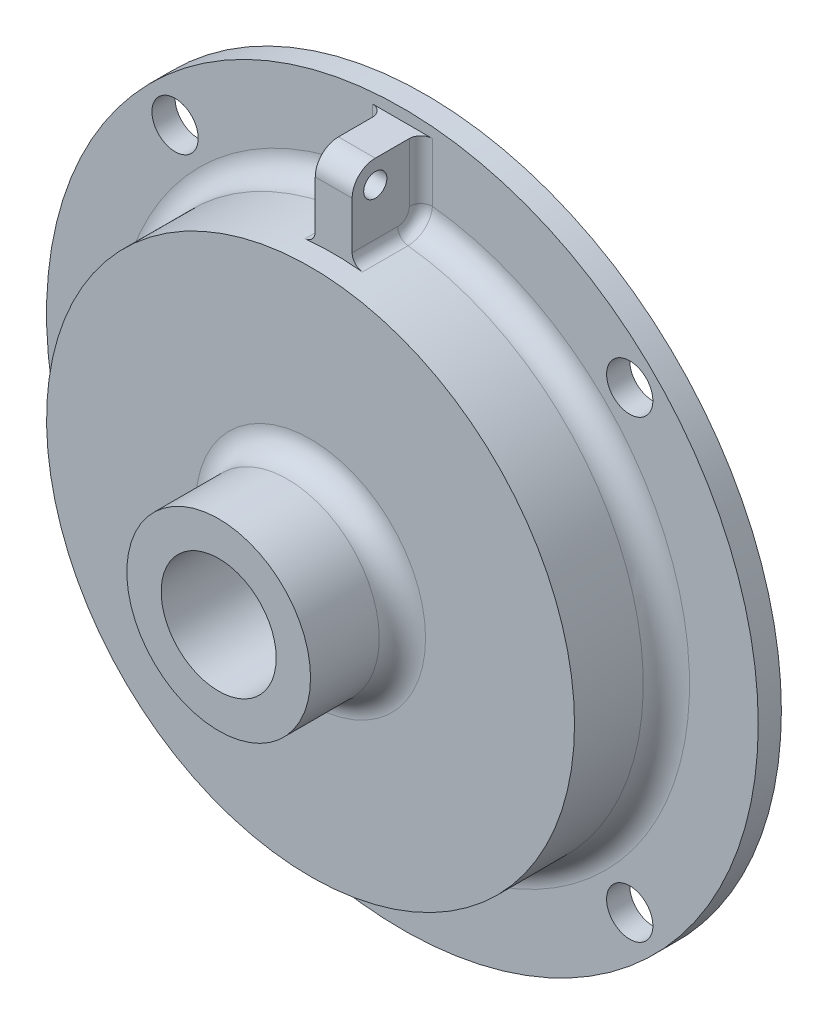
SolidWorks part; units mm, degrees
material "PW40:6:Sc:0:Re:24:"
ref_plane "Front" through (0, 0, 0) normal (0, 0, 1) x (1, 0, 0)
ref_plane "Top" through (0, 0, 0) normal (0, 1, 0) x (1, 0, 0)
ref_plane "Right" through (0, 0, 0) normal (1, 0, 0) x (0, 0, -1)
sketch "Sketch1" plane through (0, 0, 0) normal (0, 0, 1) x (1, 0, 0)
  circle A0 centre (0, 0) radius 49.2
  dimension "D1" = 98.4
extrude "Base-Extrude" add sketch "Sketch1" along normal blind 3.2
sketch "Sketch5" plane through (0, 0, 3.2) normal (0, 0, 1) x (1, 0, 0)
  line L0 (31.4309, 31.4309) -> (0, 0) construction
  line L1 (0, 0) -> (44.45, 0) construction
  circle A0 centre (0, 0) radius 44.45 construction
  circle A1 centre (31.4309, 31.4309) radius 3.2
  dimension "D1" = 88.9
  dimension "D2" = 6.4
  dimension "D3" = 45
extrude "Cut-Extrude2" cut sketch "Sketch5" against normal through all
pattern_circular "CirPattern1" count 4 every 90 about axis through (0, 0, 0) along (0, 0, 1) of "Cut-Extrude2"
sketch "Sketch2" plane through (0, 0, 3.2) normal (0, 0, 1) x (1, 0, 0)
  circle A0 centre (0, 0) radius 36.5
  dimension "D1" = 73
extrude "Boss-Extrude1" add sketch "Sketch2" along normal blind 12.7
sketch "Sketch3" plane through (0, 0, 15.9) normal (0, 0, 1) x (1, 0, 0)
  circle A0 centre (0, 0) radius 12.7
  dimension "D1" = 25.4
extrude "Boss-Extrude2" add sketch "Sketch3" along normal blind 12.7
fillet "Fillet1" radius 3.2 2 edges at (36.5, 0, 3.2) (12.7, 0, 15.9)
sketch "Sketch6" plane through (0, 0, 0) normal (0, 1, 0) x (1, 0, 0)
  line L0 (-2.55, -3.2) -> (-2.55, -12.7)
  line L1 (-39.7, -3.2) -> (39.7, -3.2) construction
  line L2 (-2.55, -3.2) -> (2.55, -3.2)
  line L3 (-49.2, -3.2) -> (49.2, -3.2) construction
  line L4 (2.55, -3.2) -> (2.55, -12.7)
  line L5 (-2.55, -12.7) -> (2.55, -12.7)
  line L6 (0, 0) -> (0, -38.11) construction
  line L7 (0, -3.2) -> (0, 0) construction
  dimension "D1" = 5.1
  dimension "D2" = 9.5
extrude "Boss-Extrude3" add sketch "Sketch6" along normal blind 47.6
sketch "Sketch4" plane through (0, 0, 28.6) normal (0, 0, 1) x (1, 0, 0)
  circle A0 centre (0, 0) radius 7.95
  dimension "D1" = 15.9
extrude "Cut-Extrude1" cut sketch "Sketch4" against normal through all
fillet "Fillet2" radius 3.2 1 edges at (0, 47.6, 12.7)
sketch "Sketch7" plane through (2.55, 0, 0) normal (1, 0, 0) x (0, 0, -1)
  circle A0 centre (-9.5, 44.4) radius 1.6
  arc A1 (-9.5, 47.6) -> (-12.7, 44.4) centre (-9.5, 44.4) ccw construction
  dimension "D1" = 3.2
extrude "Cut-Extrude3" cut sketch "Sketch7" against normal up to next
fillet "Fillet3" radius 1.6 6 edges at (2.55, 41.7131, 8.8224) (-2.55, 41.7131, 8.8224) (2.55, 43.609, 3.2) (-2.55, 36.4108, 9.55) (-2.55, 43.609, 3.2) (2.55, 36.4108, 9.55)
